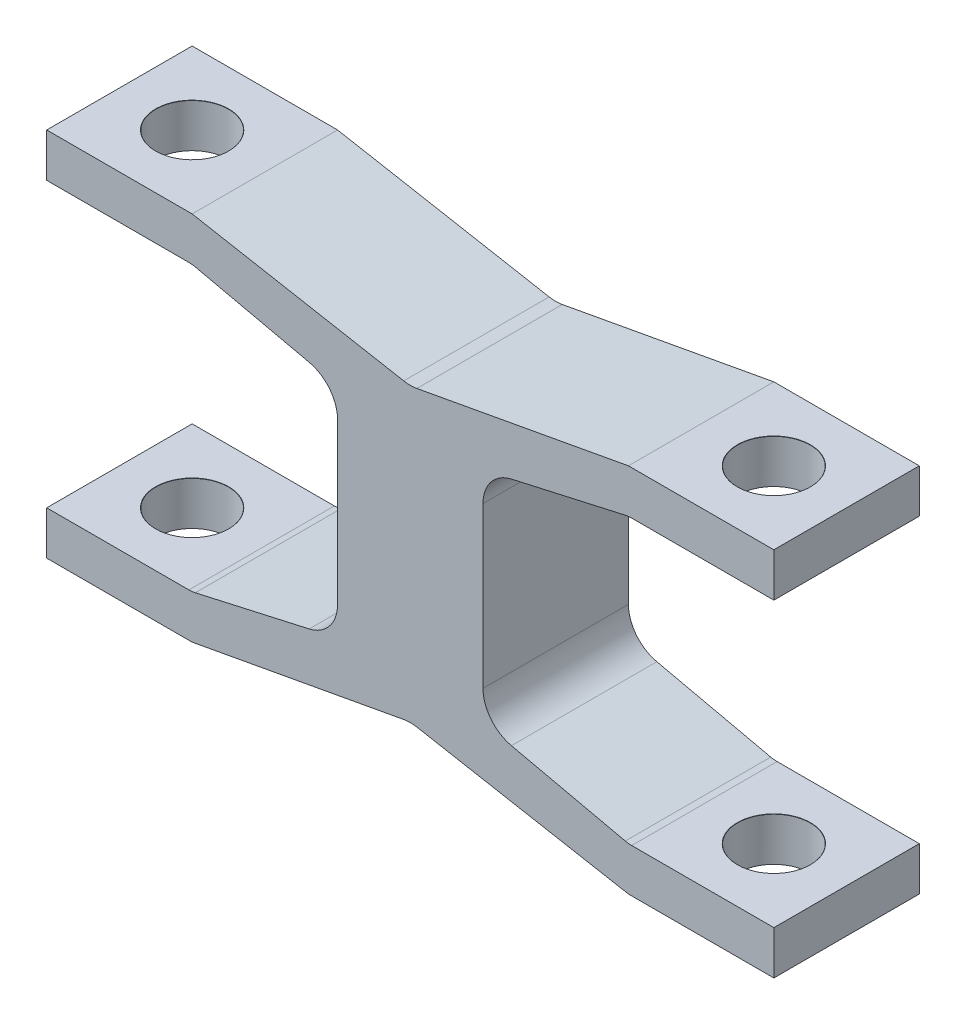
SolidWorks part; units mm, degrees
material "AISI 1045 Steel, cold drawn"
ref_plane "Front Plane" through (0, 0, 0) normal (0, 0, 1) x (1, 0, 0)
ref_plane "Top Plane" through (0, 0, 0) normal (0, 1, 0) x (1, 0, 0)
ref_plane "Right Plane" through (0, 0, 0) normal (1, 0, 0) x (0, 0, -1)
sketch "Sketch1" plane through (0, 0, 0) normal (0, 0, 1) x (1, 0, 0)
  line L0 (-69.9325, 0) -> (80.8832, 0) construction
  line L3 (-50, 19.5) -> (-50, 25.5)
  line L4 (-50, 25.5) -> (-30, 25.5)
  line L5 (-30, 25.5) -> (0, 20)
  line L6 (0, 122.3294) -> (0, -36.7286) construction
  line L20 (-50, 19.5) -> (-30, 19.5)
  line L21 (-30, 19.5) -> (-10, 15)
  line L22 (-10, 15) -> (-10, -15)
  line L23 (10, 15) -> (10, -15)
  line L24 (30, 19.5) -> (10, 15)
  line L25 (50, 19.5) -> (30, 19.5)
  line L26 (50, 19.5) -> (50, 25.5)
  line L27 (30, 25.5) -> (0, 20)
  line L28 (50, 25.5) -> (30, 25.5)
  line L29 (50, -25.5) -> (30, -25.5)
  line L30 (30, -25.5) -> (0, -20)
  line L31 (50, -19.5) -> (50, -25.5)
  line L32 (50, -19.5) -> (30, -19.5)
  line L33 (30, -19.5) -> (10, -15)
  line L34 (-30, -19.5) -> (-10, -15)
  line L35 (-50, -19.5) -> (-30, -19.5)
  line L36 (-30, -25.5) -> (0, -20)
  line L37 (-50, -25.5) -> (-30, -25.5)
  line L38 (-50, -19.5) -> (-50, -25.5)
  point P26 (10, 0)
  point P27 (-10, 0)
  dimension "D1" = 30
  dimension "D2" = 100
  dimension "D3" = 6
  dimension "D4" = 20
  dimension "D5" = 51
  dimension "D6" = 20
  dimension "D7" = 40
extrude "Boss-Extrude1" add sketch "Sketch1" along normal mid plane 20
fillet "Fillet1" radius 5 6 edges at (0, -20, 0) (0, 20, 0) (10, -15, 0) (10, 15, 0) (-10, -15, 0) (-10, 15, 0)
hole_wizard "Ø10.0mm Dowel Hole1" positions "3DSketch2" profile "Sketch3" hole size "Ø10.0" standard "ISO"
sketch3d "3DSketch2"
  line L0 (-30, 25.5, -10) -> (-50, 25.5, -10) construction
  line L1 (-50, 25.5, 10) -> (-50, 25.5, -10) construction
  line L2 (-30, -19.5, -10) -> (-50, -19.5, -10) construction
  line L3 (-50, -19.5, 10) -> (-50, -19.5, -10) construction
  line L4 (50, 25.5, -10) -> (30, 25.5, -10) construction
  line L5 (50, 25.5, 10) -> (50, 25.5, -10) construction
  line L6 (50, -19.5, -10) -> (30, -19.5, -10) construction
  line L7 (50, -19.5, 10) -> (50, -19.5, -10) construction
  point P0 (-40, 25.5, 0)
  point P2 (-40, -19.5, 0)
  point P4 (40, 25.5, 0)
  point P6 (40, -19.5, 0)
  point P11 (-40, 25.5, -10)
  point P14 (-50, 25.5, 0)
  point P17 (-40, -19.5, -10)
  point P20 (-50, -19.5, 0)
  point P23 (40, 25.5, -10)
  point P26 (50, 25.5, 0)
  point P29 (40, -19.5, -10)
  point P32 (50, -19.5, 0)
sketch "Sketch3" plane through (-40, 25.5, 0) normal (1, 0, 0) x (0, 0, 1)
  line L0 (0, 0) -> (0, 27.5043)
  line L1 (0, 27.5043) -> (5, 24.5)
  line L2 (5, 24.5) -> (5, 0.025)
  line L3 (5, 0.025) -> (5.025, 0)
  line L5 (5.025, 0) -> (0, 0)
  line L6 (-5, 0.025) -> (-5.025, 0) construction
  line L10 (0, 27.5043) -> (-5, 24.5) construction
  line L11 (0, -6.35) -> (0, 107.95) construction
  dimension "Hole Dia." = 10
  dimension "Hole Depth" = 24.5
  dimension "Near C'Sink Dia." = 10.05
  dimension "Near C'Sink Angle" = 90
  dimension "Drill Angle" = 118
fillet "Fillet2" radius 4 4 edges at (30, -19.5, 0) (-30, -19.5, 0) (-30, 19.5, 0) (30, 19.5, 0)
